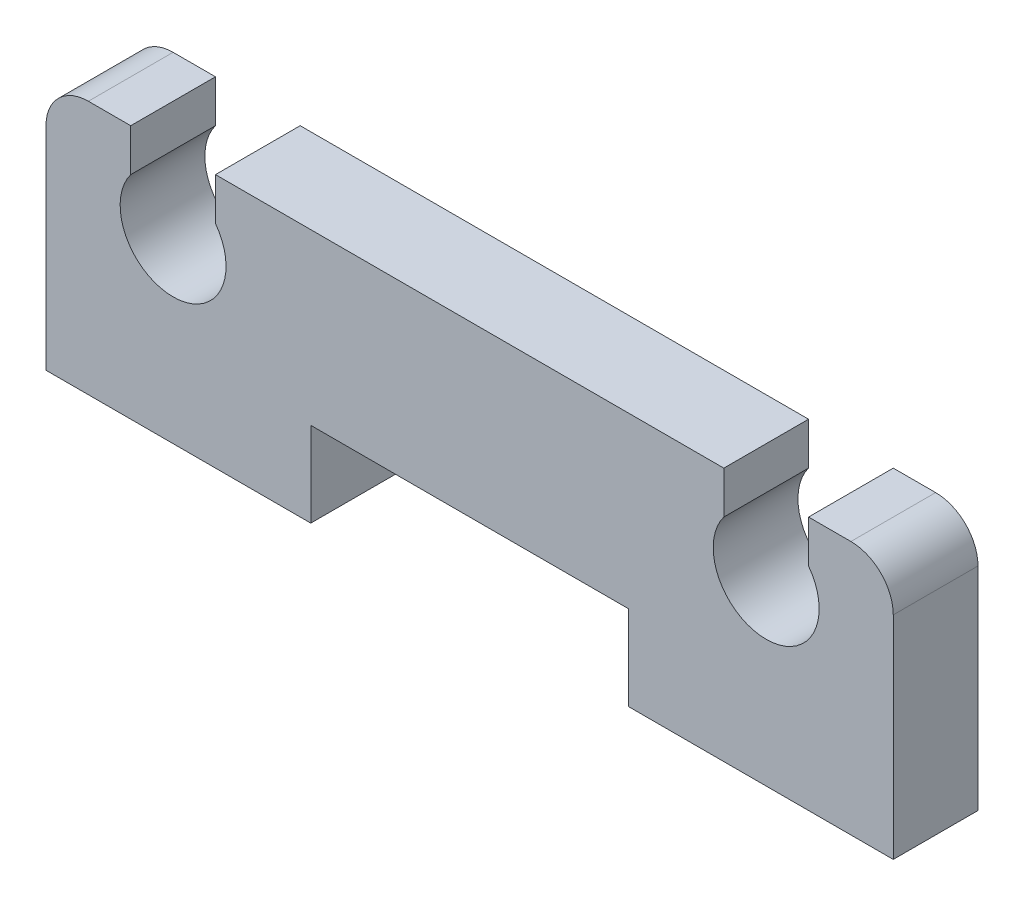
SolidWorks part; units mm, degrees
material "Acrylic (Medium-high impact)"
ref_plane "Front Plane" through (0, 0, 0) normal (0, 0, 1) x (1, 0, 0)
ref_plane "Top Plane" through (0, 0, 0) normal (0, 1, 0) x (1, 0, 0)
ref_plane "Right Plane" through (0, 0, 0) normal (1, 0, 0) x (0, 0, -1)
sketch "Model" plane through (0, 0, 0) normal (0, 0, 1) x (1, 0, 0)
  line L12 (1971.3598, 1290.9602) -> (1978.8598, 1290.9602)
  line L54 (1967.1098, 1294.9602) -> (1967.1098, 1293.9602)
  line L55 (1969.1098, 1294.9602) -> (1969.1098, 1293.9602)
  line L56 (1983.1098, 1294.9602) -> (1983.1098, 1293.9602)
  line L57 (1981.1098, 1294.9602) -> (1981.1098, 1293.9602)
  line L58 (1983.1098, 1294.9602) -> (1984.1098, 1294.9602)
  line L59 (1967.1098, 1294.9602) -> (1966.1098, 1294.9602)
  line L260 (1965.1098, 1288.9602) -> (1971.3598, 1288.9602)
  line L261 (1978.8598, 1288.9602) -> (1985.1098, 1288.9602)
  line L265 (1969.1098, 1294.9602) -> (1981.1098, 1294.9602)
  line L370 (1978.8598, 1290.9602) -> (1978.8598, 1288.9602)
  line L371 (1985.1098, 1293.9602) -> (1985.1098, 1288.9602)
  line L372 (1971.3598, 1290.9602) -> (1971.3598, 1288.9602)
  line L373 (1965.1098, 1288.9602) -> (1965.1098, 1293.9602)
  arc A16 (1966.1098, 1294.9602) -> (1965.1098, 1293.9602) centre (1966.1098, 1293.9602) ccw
  arc A17 (1985.1098, 1293.9602) -> (1984.1098, 1294.9602) centre (1984.1098, 1293.9602) ccw
  arc A18 (1967.1098, 1293.9602) -> (1969.1098, 1293.9602) centre (1968.1098, 1293.2102) ccw
  arc A51 (1981.1098, 1293.9602) -> (1983.1098, 1293.9602) centre (1982.1098, 1293.2102) ccw
extrude "Boss-Extrude1" add sketch "Model" along normal blind 2
